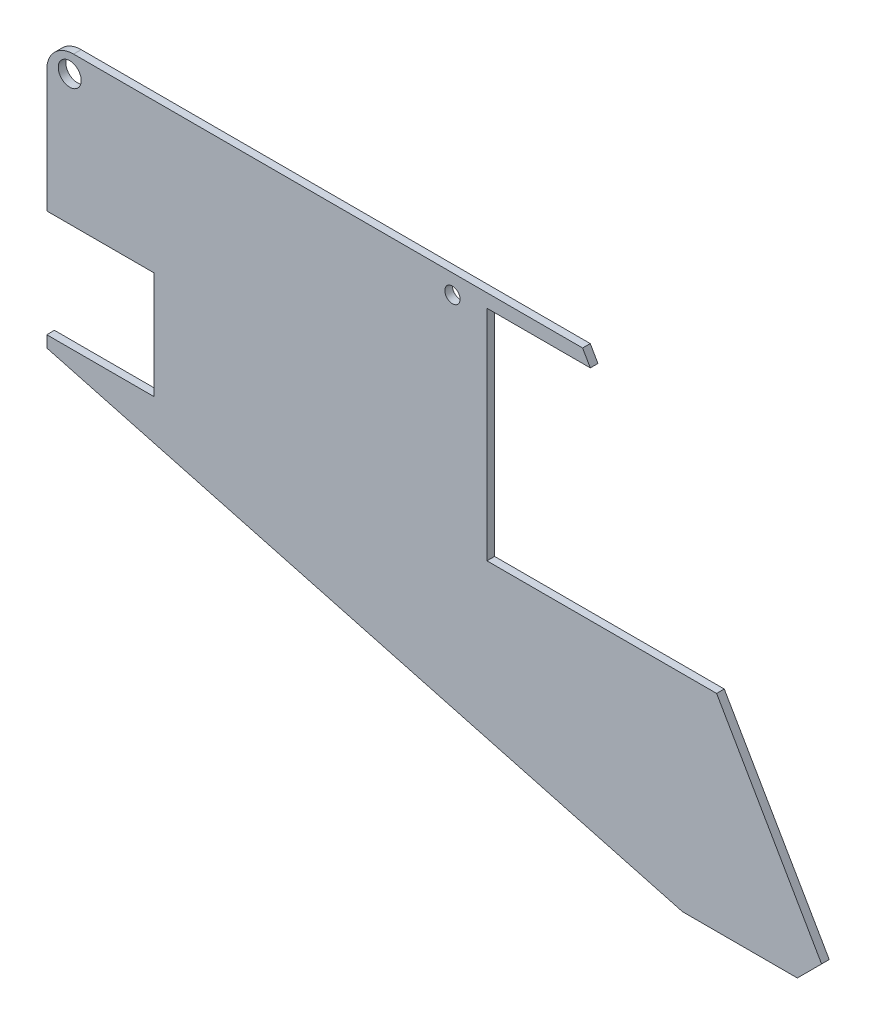
SolidWorks part; units mm, degrees
ref_plane "Front Plane" through (0, 0, 0) normal (0, 0, 1) x (1, 0, 0)
ref_plane "Top Plane" through (0, 0, 0) normal (0, 1, 0) x (1, 0, 0)
ref_plane "Right Plane" through (0, 0, 0) normal (1, 0, 0) x (0, 0, -1)
sketch "Sketch1" plane through (0, 0, 0) normal (0, 0, 1) x (1, 0, 0)
  line L4 (-350, -175) -> (480.5608, -397.5481)
  line L5 (350, 175) -> (-350, 175)
  line L6 (350, 175) -> (350, -175)
  line L7 (350, -175) -> (-350, -175)
  line L8 (-350, 175) -> (-350, -175)
  line L9 (350, 175) -> (-350, -175) construction
  line L10 (350, -175) -> (-350, 175) construction
  line L11 (680.5608, -397.5481) -> (350, 175)
  line L12 (480.5608, -397.5481) -> (680.5608, -397.5481)
  point P0 (0, 0)
  dimension "D1" = 350
  dimension "D2" = 700
  dimension "D3" = 15
  dimension "D4" = 30
  dimension "D5" = 200
extrude "Boss-Extrude2" add sketch "Sketch1" along normal mid plane 10 contours L5 L8 L7 L6 | L4 L11 L6 L7
sketch "Sketch2" plane through (0, 0, 5) normal (0, 0, 1) x (1, 0, 0)
  line L0 (350, 175) -> (-350, 175) construction
  line L1 (-350, 175) -> (-350, -175) construction
  circle A0 centre (-320, 150) radius 15
  circle A1 centre (180, 150) radius 10
  dimension "D1" = 30
  dimension "D5" = 20
  dimension "D2" = 25
  dimension "D3" = 30
  dimension "D4" = 500
  dimension "D6" = 25
extrude "Cut-Extrude1" cut sketch "Sketch2" against normal blind 10
fillet "Fillet1" radius 35 1 edges at (-350, 175, 0)
sketch "Sketch3" plane through (0, 0, 5) normal (0, 0, 1) x (1, 0, 0)
  line L0 (-350, 140) -> (-350, -175) construction
  line L1 (-350, -20) -> (-210, -20)
  line L2 (-350, -20) -> (-350, -160)
  line L3 (-350, -160) -> (-210, -160)
  line L4 (-210, -20) -> (-210, -160)
  line L5 (225.1111, 157.4871) -> (225.1111, -128.3013)
  line L7 (225.1111, -128.3013) -> (525.1111, -128.3013)
  line L8 (680.5608, -397.5481) -> (350, 175) construction
  line L10 (360.1111, 157.4871) -> (525.1111, -128.3013)
  line L11 (225.1111, 157.4871) -> (360.1111, 157.4871)
  line L12 (350, 175) -> (-315, 175) construction
  dimension "D1" = 140
  dimension "D2" = 140
  dimension "D3" = 20
  dimension "D4" = 575.1111
  dimension "D5" = 300
  dimension "D6" = 135
  dimension "D7" = 17.5129
extrude "Cut-Extrude2" cut sketch "Sketch3" against normal through all
chamfer "Chamfer1" distance 50 angle 45 1 edges at (680.5608, -397.5481, 0)
